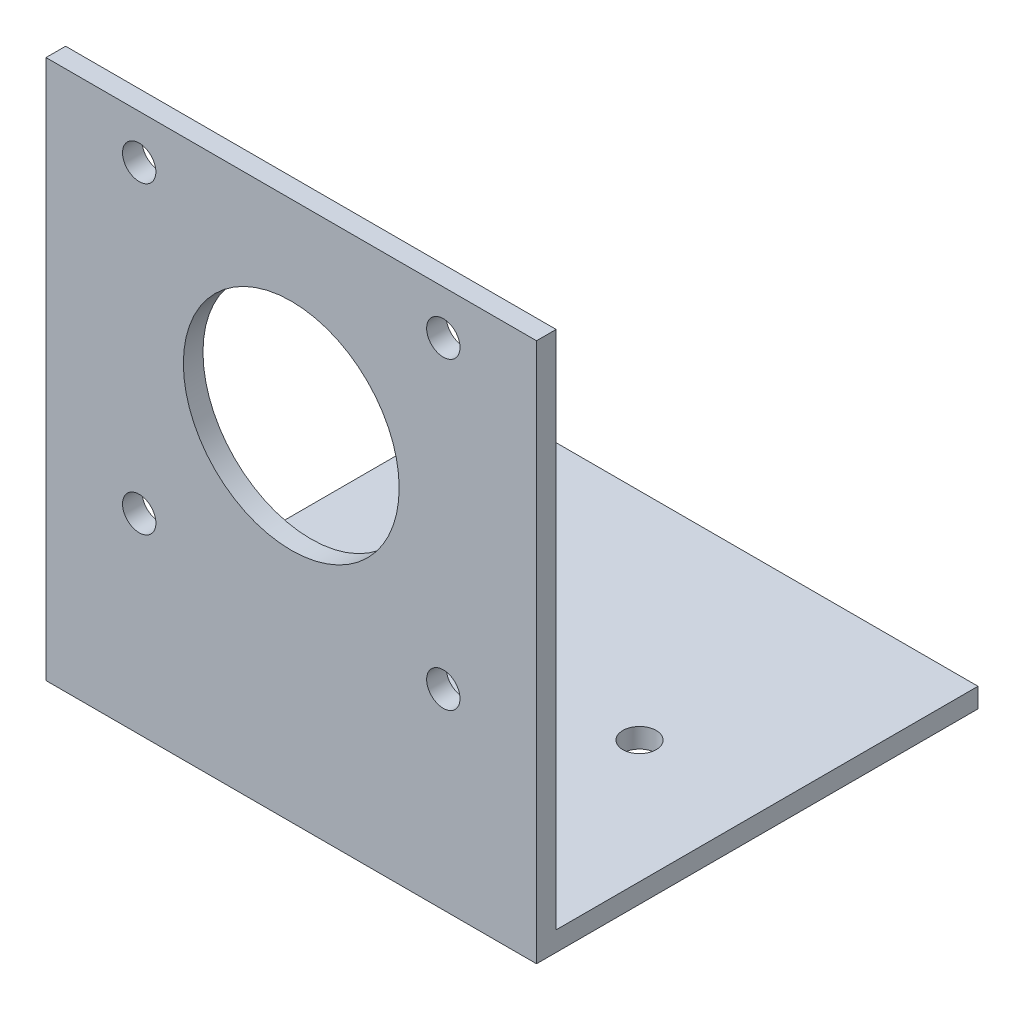
SolidWorks part; units mm, degrees
ref_plane "Front Plane" through (0, 0, 0) normal (0, 0, 1) x (1, 0, 0)
ref_plane "Top Plane" through (0, 0, 0) normal (0, 1, 0) x (1, 0, 0)
ref_plane "Right Plane" through (0, 0, 0) normal (1, 0, 0) x (0, 0, -1)
sketch "Sketch1" plane through (0, 0, 0) normal (0, 0, 1) x (1, 0, 0)
  line L1 (-25, 0) -> (25, 0)
  line L2 (-25, 0) -> (-25, 55)
  line L3 (-25, 55) -> (25, 55)
  line L4 (25, 0) -> (25, 55)
  dimension "D1" = 25
  dimension "D2" = 25
  dimension "D3" = 55
extrude "Boss-Extrude1" add sketch "Sketch1" against normal blind 2
sketch "Sketch2" plane through (0, 0, 0) normal (0, 0, 1) x (1, 0, 0)
  line L1 (-25, 0) -> (25, 0)
  line L2 (-25, 0) -> (-25, 2)
  line L3 (-25, 2) -> (25, 2)
  line L4 (25, 0) -> (25, 2)
  dimension "D1" = 25
  dimension "D2" = 25
  dimension "D3" = 2
extrude "Boss-Extrude2" add sketch "Sketch2" against normal blind 45
sketch "Sketch3" plane through (0, 0, 0) normal (0, 0, 1) x (1, 0, 0)
  circle A0 centre (-15.5, 19.5) radius 1.7
  circle A1 centre (-15.5, 50.5) radius 1.7
  circle A2 centre (15.5, 19.5) radius 1.7
  circle A3 centre (15.5, 50.5) radius 1.7
  dimension "D1" = 3.4
  dimension "D2" = 15.5
  dimension "D3" = 15.5
  dimension "D4" = 19.5
  dimension "D5" = 50.5
extrude "Cut-Extrude1" cut sketch "Sketch3" along normal through all and the other way through all
sketch "Sketch4" plane through (0, 0, 0) normal (0, 0, 1) x (1, 0, 0)
  circle A0 centre (0, 35) radius 11
  dimension "D1" = 22
  dimension "D2" = 35
extrude "Lo_tam_D22" cut sketch "Sketch4" along normal through all and the other way through all
sketch "Sketch5" plane through (0, 0, 0) normal (0, 1, 0) x (1, 0, 0)
  circle A0 centre (-12.5, 23) radius 1.7
  circle A1 centre (12.5, 23) radius 1.7
  dimension "D1" = 3.4
  dimension "D2" = 12.5
  dimension "D3" = 12.5
  dimension "D4" = 23
extrude "Hai_lo_chan_M3" cut sketch "Sketch5" along normal through all and the other way through all
